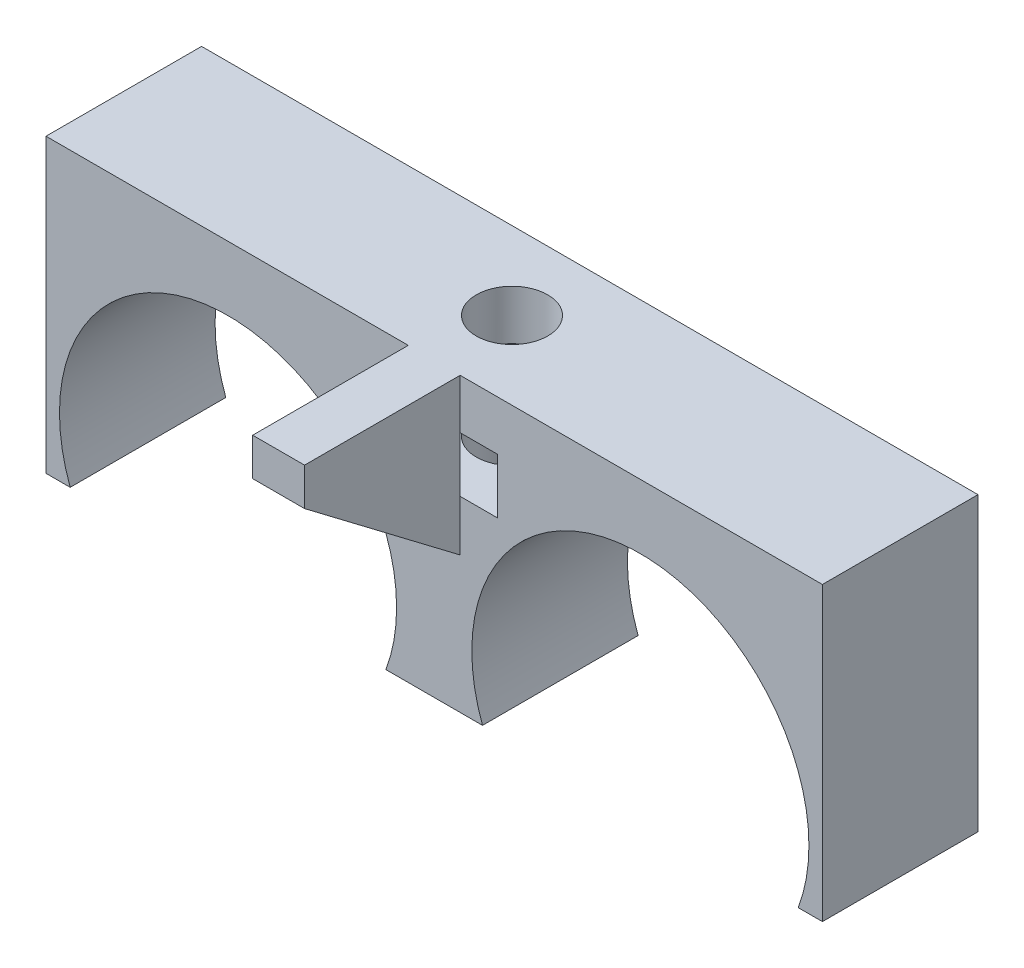
SolidWorks part; units mm, degrees
ref_plane "Front Plane" through (0, 0, 0) normal (0, 0, 1) x (1, 0, 0)
ref_plane "Top Plane" through (0, 0, 0) normal (0, 1, 0) x (1, 0, 0)
ref_plane "Right Plane" through (0, 0, 0) normal (1, 0, 0) x (0, 0, -1)
sketch "Sketch1" plane through (0, 0, 0) normal (0, 0, 1) x (1, 0, 0)
  line L0 (-25.2621, 6.4008) -> (-23.5066, 6.4008) construction
  line L1 (-3.3136, 6.4008) -> (-9.1868, 6.4008)
  line L2 (-23.5066, 6.4008) -> (-25.2621, 6.4008)
  line L3 (-25.2621, 6.4008) -> (-25.2621, 19.939)
  line L4 (-25.2621, 19.939) -> (12.7617, 19.939)
  line L5 (12.7617, 19.939) -> (12.7617, 6.4008)
  line L6 (12.7617, 6.4008) -> (11.0062, 6.4008)
  line L7 (12.3807, 6.7818) -> (11.5768, 6.7818)
  line L8 (-3.8842, 6.7818) -> (-8.6162, 6.7818)
  line L9 (-24.0772, 6.7818) -> (-24.8811, 6.7818)
  line L10 (-24.8811, 6.7818) -> (-24.8811, 19.558)
  line L11 (-24.8811, 19.558) -> (12.3807, 19.558)
  line L12 (12.3807, 19.558) -> (12.3807, 6.7818)
  line L13 (-24.8811, 6.7818) -> (-25.2621, 6.7818)
  line L14 (12.3807, 6.7818) -> (12.7617, 6.7818)
  arc A0 (11.0062, 6.4008) -> (-3.3136, 6.4008) centre (3.8463, 9.6774) ccw
  arc A1 (-9.1868, 6.4008) -> (-23.5066, 6.4008) centre (-16.3467, 9.6774) ccw
  arc A2 (-9.1868, 6.4008) -> (-23.5066, 6.4008) centre (-16.3467, 9.6774) ccw construction
  arc A3 (11.5768, 6.7818) -> (-3.8842, 6.7818) centre (3.8463, 9.6774) ccw
  arc A4 (-8.6162, 6.7818) -> (-24.0772, 6.7818) centre (-16.3467, 9.6774) ccw
  dimension "D1" = 0.381
extrude "Boss-Extrude1" add sketch "Sketch1" along normal blind 7.62 contours A4 L8 A3 L7 L12 L11 L10 L9 | L12 L14 L5 L4 L3 L13 L10 L11
sketch "Sketch2" plane through (0, 19.939, 0) normal (0, 1, 0) x (1, 0, 0)
  line L0 (-6.2502, -7.62) -> (-6.2502, 0)
  line L1 (-25.2621, -7.62) -> (12.7617, -7.62) construction
  line L2 (-25.2621, 0) -> (12.7617, 0) construction
  circle A0 centre (-6.2502, -3.81) radius 1.75
  dimension "D1" = 3.5
extrude "Cut-Extrude1" cut sketch "Sketch2" against normal blind 8 and the other way blind 1.143 contours L0 A0 | L0 A0
sketch "Sketch3" plane through (0, 0, 7.62) normal (0, 0, 1) x (1, 0, 0)
  line L0 (-6.2502, 19.939) -> (-6.2502, 18.6483)
  line L1 (-25.2621, 19.939) -> (12.7617, 19.939) construction
  line L8 (-9.3502, 15.9483) -> (-3.1502, 15.9483)
  line L9 (-9.3502, 15.9483) -> (-9.3502, 18.6483)
  line L10 (-9.3502, 18.6483) -> (-3.1502, 18.6483)
  line L11 (-3.1502, 15.9483) -> (-3.1502, 18.6483)
  point P8 (-6.2502, 18.6483)
  dimension "D1" = 6.2
  dimension "D2" = 2.7
  dimension "D3" = 0
extrude "Cut-Extrude2" cut sketch "Sketch3" against normal blind 7.62 contours L8 L11 L10 L9
sketch "Sketch4" plane through (0, 19.939, 0) normal (0, 1, 0) x (1, 0, 0)
  line L1 (12.7617, -7.62) -> (-25.2621, -7.62)
  line L2 (12.7617, -7.62) -> (12.7617, 0)
  line L3 (12.7617, 0) -> (-25.2621, 0)
  line L4 (-25.2621, -7.62) -> (-25.2621, 0)
  circle A3 centre (-6.2502, -3.81) radius 1.75
extrude "Boss-Extrude2" add sketch "Sketch4" along normal blind 1.143
sketch "Sketch5" plane through (0, 0, 7.62) normal (0, 0, 1) x (1, 0, 0)
  line L0 (-25.2621, 21.082) -> (12.7617, 21.082) construction
  line L2 (-7.5202, 21.082) -> (-4.9802, 21.082)
  line L3 (-7.5202, 21.082) -> (-7.5202, 13.462)
  line L4 (-7.5202, 13.462) -> (-4.9802, 13.462)
  line L5 (-4.9802, 21.082) -> (-4.9802, 13.462)
  point P0 (-6.2502, 21.082)
  point P1 (-7.5202, 21.082)
  dimension "D1" = 1.27
  dimension "D2" = 1.27
  dimension "D3" = 7.62
extrude "Boss-Extrude3" add sketch "Sketch5" along normal blind 7.62
sketch "Sketch6" plane through (-4.9802, 0, 0) normal (1, 0, 0) x (0, 0, -1)
  line L0 (-7.62, 21.082) -> (-15.24, 21.082)
  line L1 (-15.24, 21.082) -> (-15.24, 19.2385)
  line L2 (-15.24, 13.462) -> (-15.24, 21.082) construction
  line L3 (-15.24, 19.2385) -> (-7.62, 13.462)
  line L4 (-7.62, 13.462) -> (-7.62, 21.082)
  line L5 (-15.24, 19.2385) -> (-15.24, 13.462)
  line L6 (-15.24, 13.462) -> (-7.62, 13.462)
  line L7 (-15.24, 13.462) -> (-15.24, 19.2385)
  line M5 (-15.24, 21.082) -> (-15.24, 13.462)
  line M6 (-15.24, 13.462) -> (-7.62, 13.462)
extrude "Cut-Extrude3" cut sketch "Sketch6" against normal blind 7.62 contours L3 M5 M6
